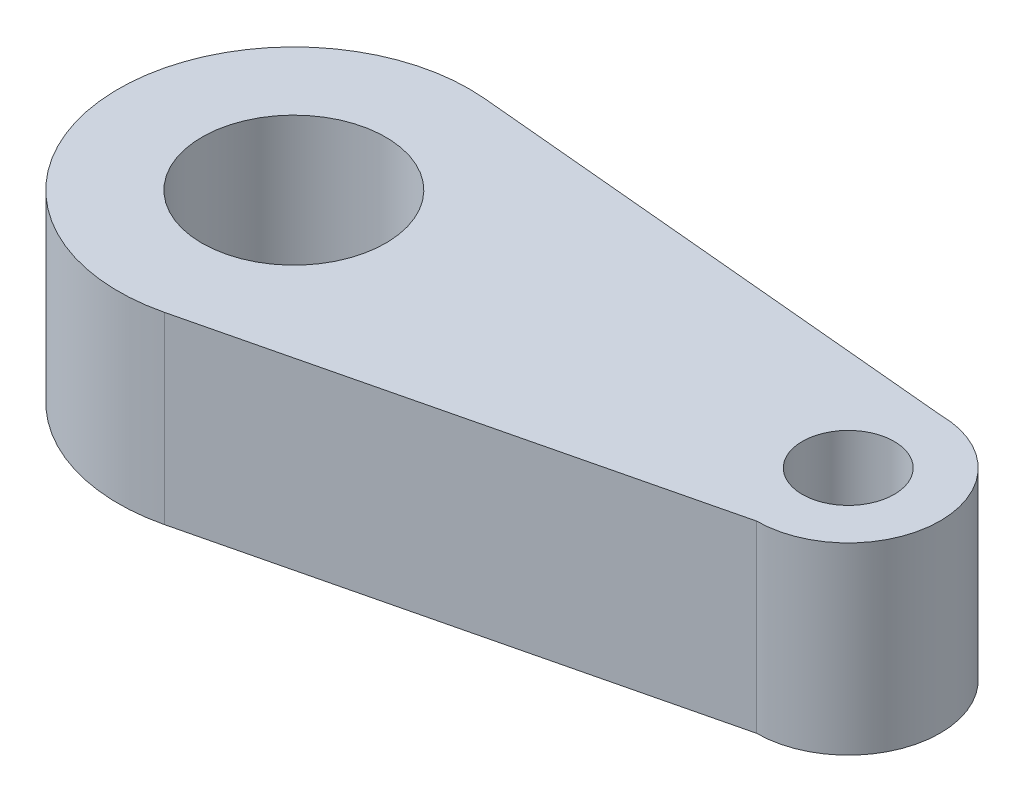
SolidWorks part; units mm, degrees
ref_plane "Front Plane" through (0, 0, 0) normal (0, 0, 1) x (1, 0, 0)
ref_plane "Top Plane" through (0, 0, 0) normal (0, 1, 0) x (1, 0, 0)
ref_plane "Right Plane" through (0, 0, 0) normal (1, 0, 0) x (0, 0, -1)
sketch "Sketch1" plane through (0, 0, 0) normal (0, 1, 0) x (1, 0, 0)
  line L0 (0, 0) -> (-1, 0) construction
  line L3 (0, 2) -> (-10.9165, 3.0038)
  line L5 (-10.3687, -4.5078) -> (0, -2)
  arc A0 (0, -2) -> (0, 2) centre (0, 0) ccw
  circle A3 centre (0, 0) radius 1
  circle A4 centre (-11.2661, -0.7974) radius 2
  arc A5 (-10.9165, 3.0038) -> (-10.3687, -4.5078) centre (-11.2661, -0.7974) ccw
  point P3 (-6.5, 0)
  dimension "D2" = 2
extrude "Boss-Extrude1" add sketch "Sketch1" along normal blind 4
